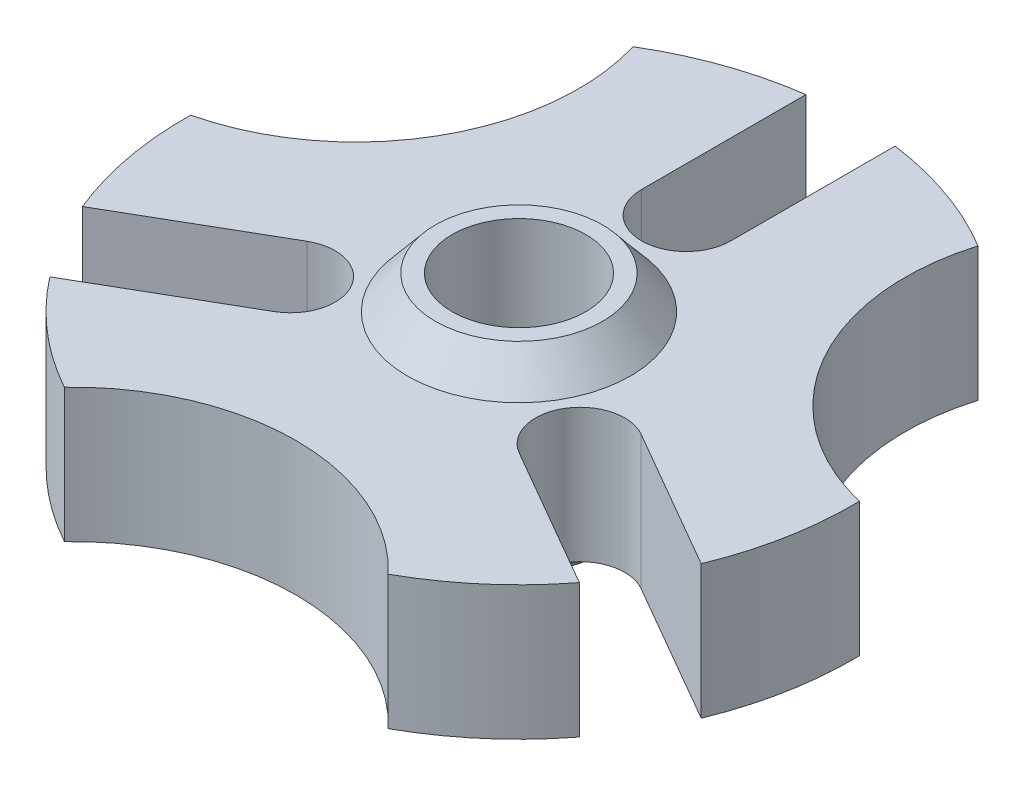
SolidWorks part; units mm, degrees
ref_plane "前视基准面" through (0, 0, 0) normal (0, 0, 1) x (1, 0, 0)
ref_plane "上视基准面" through (0, 0, 0) normal (0, 1, 0) x (1, 0, 0)
ref_plane "右视基准面" through (0, 0, 0) normal (1, 0, 0) x (0, 0, -1)
other "Configuration Table"
sketch "草图1" plane through (0, 0, 0) normal (0, 1, 0) x (1, 0, 0)
  line L0 (0, 43.8521) -> (0, -51.3765) construction
  line L1 (-10.9904, -10.9641) -> (-23.7488, -18.3302)
  line L2 (-14.9904, -4.0359) -> (-27.7488, -11.402)
  line L3 (0, 0) -> (-39.6685, -22.9026) construction
  line L4 (4, 15) -> (4, 29.7321)
  line L5 (-4, 15) -> (-4, 29.7321)
  line L6 (10.9904, -10.9641) -> (23.7488, -18.3302)
  line L7 (14.9904, -4.0359) -> (27.7488, -11.402)
  circle A0 centre (0, 0) radius 6
  circle A1 centre (0, 0) radius 15 construction
  arc A2 (14.5237, -26.25) -> (23.7488, -18.3302) centre (0, 0) ccw
  arc A3 (14.5237, -26.25) -> (-14.5237, -26.25) centre (0, -40) ccw
  arc A4 (-10.9904, -10.9641) -> (-14.9904, -4.0359) centre (-12.9904, -7.5) ccw
  arc A5 (-23.7488, -18.3302) -> (-14.5237, -26.25) centre (0, 0) ccw
  arc A6 (-4, 15) -> (4, 15) centre (0, 15) ccw
  arc A7 (-29.995, 0.5471) -> (-15.4713, 25.7029) centre (-34.641, 20) ccw
  arc A8 (14.9904, -4.0359) -> (10.9904, -10.9641) centre (12.9904, -7.5) ccw
  arc A9 (15.4713, 25.7029) -> (29.995, 0.5471) centre (34.641, 20) ccw
  arc A10 (-29.995, 0.5471) -> (-27.7488, -11.402) centre (0, 0) ccw
  arc A11 (-4, 29.7321) -> (-15.4713, 25.7029) centre (0, 0) ccw
  arc A12 (15.4713, 25.7029) -> (4, 29.7321) centre (0, 0) ccw
  arc A13 (27.7488, -11.402) -> (29.995, 0.5471) centre (0, 0) ccw
  point P35 (0, 0)
  dimension "D1" = 60
  dimension "D2" = 30
  dimension "D3" = 12
  dimension "D5" = 40
  dimension "D7" = 8
  dimension "D4" = 40
  dimension "D6" = 60
  dimension "D8" = 0
  dimension "D9" = 3
extrude "凸台-拉伸2" add sketch "草图1" along normal mid plane 12
sketch "草图3" plane through (0, 0, 0) normal (1, 0, 0) x (0, 0, -1)
  line L0 (0, 16.131) -> (0, -17.5354) construction
  line L1 (-10, 6) -> (-7.5, 9)
  line L4 (0.5471, 6) -> (-11.402, 6) construction
  line L5 (-10, 6) -> (-6, 6)
  line L6 (-7.5, 9) -> (-6, 9)
  line L7 (-6, 9) -> (-6, 6)
  point P4 (-7.5, 9)
  point P6 (-10, 6)
  point P14 (-6, 9)
  point P15 (0, 0)
  point P16 (0, 0)
  point P17 (0, 0)
  point P18 (-6.0003, 6)
  dimension "D1" = 15
  dimension "D2" = 20
  dimension "D3" = 3
  dimension "D4" = 12
revolve "旋转2" add sketch "草图3" angle 360 about L0
mirror "镜向2" about plane through (0, 0, 0) normal (0, 1, 0) of "旋转2"
